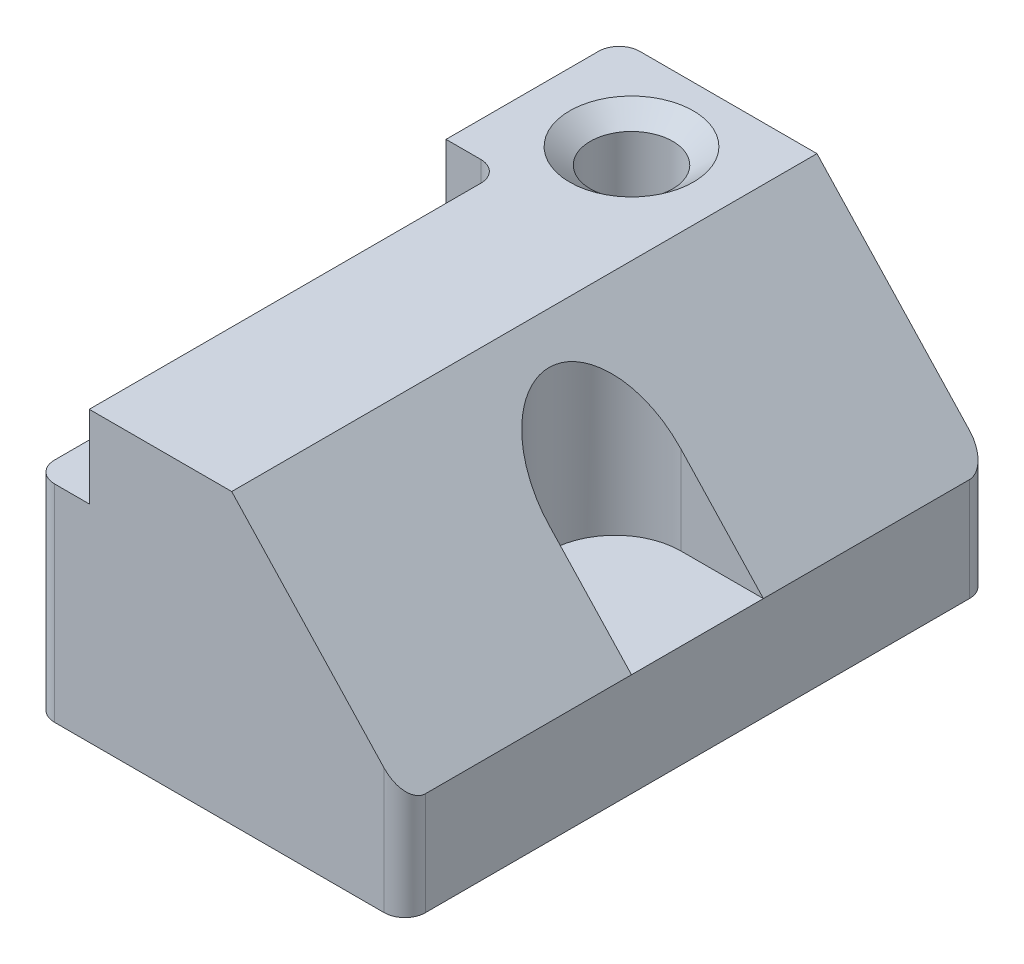
SolidWorks part; units mm, degrees
ref_plane "Front Plane" through (0, 0, 0) normal (0, 0, 1) x (1, 0, 0)
ref_plane "Top Plane" through (0, 0, 0) normal (0, 1, 0) x (1, 0, 0)
ref_plane "Right Plane" through (0, 0, 0) normal (1, 0, 0) x (0, 0, -1)
sketch "Sketch1" plane through (0, 0, 0) normal (0, 0, 1) x (1, 0, 0)
  line L0 (-45, -35) -> (45, -35)
  line L1 (45, -35) -> (45, -10)
  line L2 (45, -10) -> (3, 35)
  line L5 (-45, 35) -> (-45, -35)
  line L6 (-45, 35) -> (3, 35)
  point P2 (0, -35)
  dimension "D1" = 90
  dimension "D2" = 70
  dimension "D3" = 25
  dimension "D4" = 48
  dimension "D5" = 35
  dimension "D6" = 45
extrude "Boss-Extrude1" add sketch "Sketch1" against normal blind 142
sketch "Sketch2" plane through (0, 0, 0) normal (0, 0, 1) x (1, 0, 0)
  line L0 (-31.5617, 35) -> (-31.5617, 15.1095)
  line L1 (3, 35) -> (-45, 35) construction
  line L2 (-31.5617, 15.1095) -> (-45, 15.1095)
  line L3 (-45, 35) -> (-45, -35) construction
  line L4 (-45, 15.1095) -> (-45, 35)
  line L5 (-45, 35) -> (-31.5617, 35)
extrude "Cut-Extrude1" cut sketch "Sketch2" against normal blind 100
sketch "Sketch4" plane through (0, 35, 0) normal (0, 1, 0) x (1, 0, 0)
  line L0 (3, 142) -> (3, 0) construction
  line L4 (3, 142) -> (-45, 142) construction
  circle A0 centre (-21, 121) radius 10
  point P6 (-21, 142)
  dimension "D1" = 24
  dimension "D2" = 20
  dimension "D3" = 21
extrude "Cut-Extrude2" cut sketch "Sketch4" against normal blind 100
sketch3d "3DSketch2"
  line L0 (45, -10, -55) -> (25, -10, -55)
  line L1 (45, -10, -142) -> (45, -10, 0) construction
  line L2 (25, -10, -87) -> (45, -10, -87)
  line L3 (45, -10, -55) -> (45, -10, -87)
  arc A0 (25, -10, -55) -> (25, -10, -87) centre (25, -10, -71) ccw
  point P5 (45, -10, -142)
  point P6 (45, -10, -142)
  point P8 (45, -10, -142)
  point P10 (45, -10, 0)
  point P11 (45, -10, -142)
  point P12 (45, -10, -142)
  point P13 (45, -10, -142)
  point P16 (25, -26, -71)
  dimension "D2" = 55
  dimension "D1" = 55
  dimension "D3" = 20
  dimension "D4" = 20
extrude "Cut-Extrude3" cut sketch "3DSketch2" along direction (0, 1, 0) on the side of the normal blind 100
chamfer "Chamfer1" distance 5 angle 38 2 edges at (-31, 35, -121) (-21, -35, -131)
fillet "Fillet5" radius 5 1 edges at (-31.5617, 25.0547, -100)
fillet "Fillet6" radius 5 2 edges at (45, -22.5, 0) (-45, -9.9453, 0)
fillet "Fillet7" radius 5 2 edges at (-45, 0, -142) (45, -22.5, -142)
